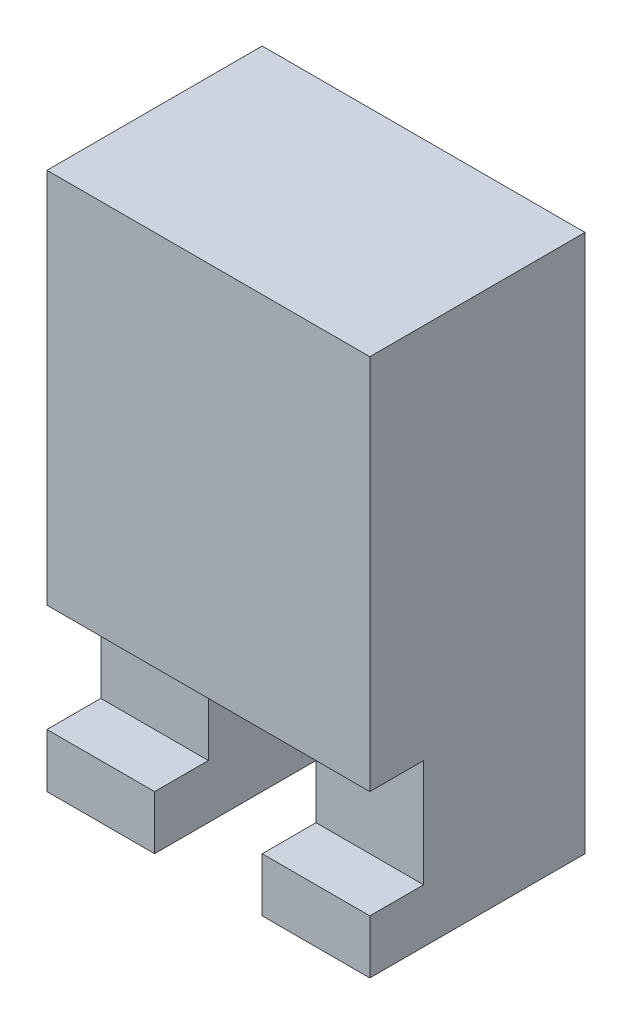
SolidWorks part; units mm, degrees
ref_plane "Front Plane" through (0, 0, 0) normal (0, 0, 1) x (1, 0, 0)
ref_plane "Top Plane" through (0, 0, 0) normal (0, 1, 0) x (1, 0, 0)
ref_plane "Right Plane" through (0, 0, 0) normal (1, 0, 0) x (0, 0, -1)
sketch "Sketch2" plane through (0, 0, 0) normal (0, 1, 0) x (1, 0, 0)
  line L0 (-1.5, -1) -> (-1.5, 1)
  line L1 (-1.5, -1) -> (1.5, -1)
  line L2 (-1.5, 1) -> (1.5, 1)
  line L3 (1.5, -1) -> (1.5, 1)
  line L4 (-1.5, -1) -> (1.5, 1) construction
  line L5 (-1.5, 1) -> (1.5, -1) construction
  point P1 (0, 0)
  dimension "D1" = 3
  dimension "D2" = 2
extrude "Boss-Extrude1" add sketch "Sketch2" along normal blind 5
sketch "Sketch3" plane through (0, 0, 1) normal (0, 0, 1) x (1, 0, 0)
  line L0 (-1.5, 0.5) -> (1.5, 0.5)
  line L1 (-1.5, 0.5) -> (-1.5, 1.5)
  line L2 (1.5, 0.5) -> (1.5, 1.5)
  line L3 (-1.5, 1.5) -> (1.5, 1.5)
  line L4 (-1.5, 5) -> (-1.5, 0) construction
  line L5 (1.5, 5) -> (1.5, 0) construction
  line L6 (-1.5, 0) -> (1.5, 0) construction
  dimension "D1" = 0.5
  dimension "D2" = 1
extrude "Cut-Extrude1" cut sketch "Sketch3" against normal blind 0.5
sketch "Sketch4" plane through (0, 0, -1) normal (0, 0, -1) x (-1, 0, 0)
  line L0 (-0.5, 0) -> (0.5, 0)
  line L1 (-0.5, 0) -> (-0.5, 1.5)
  line L2 (0.5, 0) -> (0.5, 1.5)
  line L3 (-0.5, 1.5) -> (0.5, 1.5)
  line L4 (-1.5, 0) -> (1.5, 0) construction
  line L5 (-1.5, 5) -> (-1.5, 0) construction
  dimension "D1" = 1
  dimension "D2" = 1
  dimension "D3" = 1.5
extrude "Cut-Extrude2" cut sketch "Sketch4" against normal blind 5
